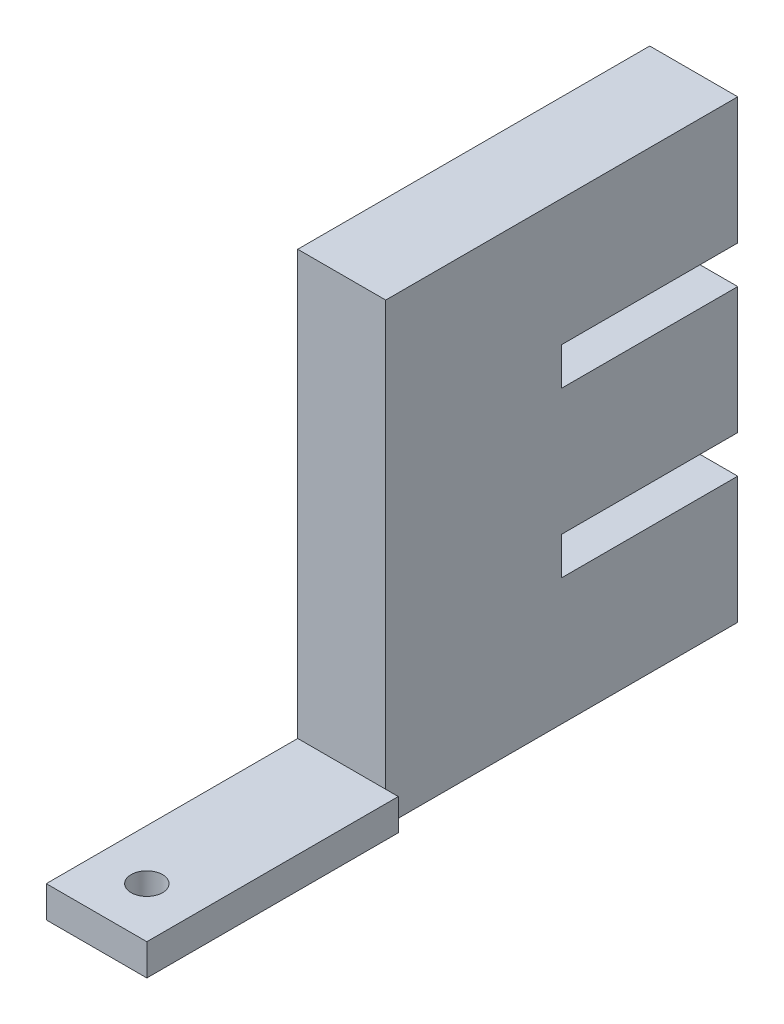
SolidWorks part; units mm, degrees
ref_plane "Front Plane" through (0, 0, 0) normal (0, 0, 1) x (1, 0, 0)
ref_plane "Top Plane" through (0, 0, 0) normal (0, 1, 0) x (1, 0, 0)
ref_plane "Right Plane" through (0, 0, 0) normal (1, 0, 0) x (0, 0, -1)
ref_plane "PZ_m16_000" through (0, 0, -16) normal (0, 0, 1) x (1, 0, 0)
sketch "S_box1" plane through (0, 0, -16) normal (0, 0, 1) x (1, 0, 0)
  line L0 (-4, -4.5) -> (4, -4.5)
  line L1 (4, -4.5) -> (4, -2)
  line L2 (4, -2) -> (-4, -2)
  line L3 (-4, -2) -> (-4, -4.5)
  dimension "P1" = 4
  dimension "P2" = 4.5
  dimension "P3" = 4
  dimension "P4" = 4.5
  dimension "P5" = 4
  dimension "P6" = 2
  dimension "P7" = 4
  dimension "P8" = 2
extrude "Boss_1" add sketch "S_box1" along normal blind 20
ref_plane "PZ_m44_000" through (0, 0, -44) normal (0, 0, 1) x (1, 0, 0)
sketch "S_box2" plane through (0, 0, -44) normal (0, 0, 1) x (1, 0, 0)
  line L0 (-4, -4.5) -> (3, -4.5)
  line L1 (3, -4.5) -> (3, 31.7)
  line L2 (3, 31.7) -> (-4, 31.7)
  line L3 (-4, 31.7) -> (-4, -4.5)
  dimension "P1" = 4
  dimension "P2" = 4.5
  dimension "P3" = 3
  dimension "P4" = 4.5
  dimension "P5" = 3
  dimension "P6" = 31.7
  dimension "P7" = 4
  dimension "P8" = 31.7
extrude "Boss_2" add sketch "S_box2" along normal blind 28
ref_plane "PY_m4_600" through (0, -4.6, 0) normal (0, 1, 0) x (1, 0, 0)
sketch "S_hole3" plane through (0, -4.6, 0) normal (0, 1, 0) x (1, 0, 0)
  circle A0 centre (0, 0) radius 1.25
  dimension "D1_S_hole3" = 2.5
extrude "Hole_3" cut sketch "S_hole3" along normal blind 2.7
ref_plane "PZ_m44_100" through (0, 0, -44.1) normal (0, 0, 1) x (1, 0, 0)
sketch "S_cut4" plane through (0, 0, -44.1) normal (0, 0, 1) x (1, 0, 0)
  line L0 (-4.1, 5.57) -> (3.1, 5.57)
  line L1 (3.1, 5.57) -> (3.1, 8.57)
  line L2 (3.1, 8.57) -> (-4.1, 8.57)
  line L3 (-4.1, 8.57) -> (-4.1, 5.57)
  dimension "P1" = 4.1
  dimension "P2" = 5.57
  dimension "P3" = 3.1
  dimension "P4" = 5.57
  dimension "P5" = 3.1
  dimension "P6" = 8.57
  dimension "P7" = 4.1
  dimension "P8" = 8.57
extrude "Pocket_4" cut sketch "S_cut4" along normal blind 14.1
sketch "S_cut5" plane through (0, 0, -44.1) normal (0, 0, 1) x (1, 0, 0)
  line L0 (-4.1, 18.63) -> (3.1, 18.63)
  line L1 (3.1, 18.63) -> (3.1, 21.63)
  line L2 (3.1, 21.63) -> (-4.1, 21.63)
  line L3 (-4.1, 21.63) -> (-4.1, 18.63)
  dimension "P1" = 4.1
  dimension "P2" = 18.63
  dimension "P3" = 3.1
  dimension "P4" = 18.63
  dimension "P5" = 3.1
  dimension "P6" = 21.63
  dimension "P7" = 4.1
  dimension "P8" = 21.63
extrude "Pocket_5" cut sketch "S_cut5" along normal blind 14.1
equation "\"plate_t\" = 3"
equation "\"clearance\" = 0.4"
